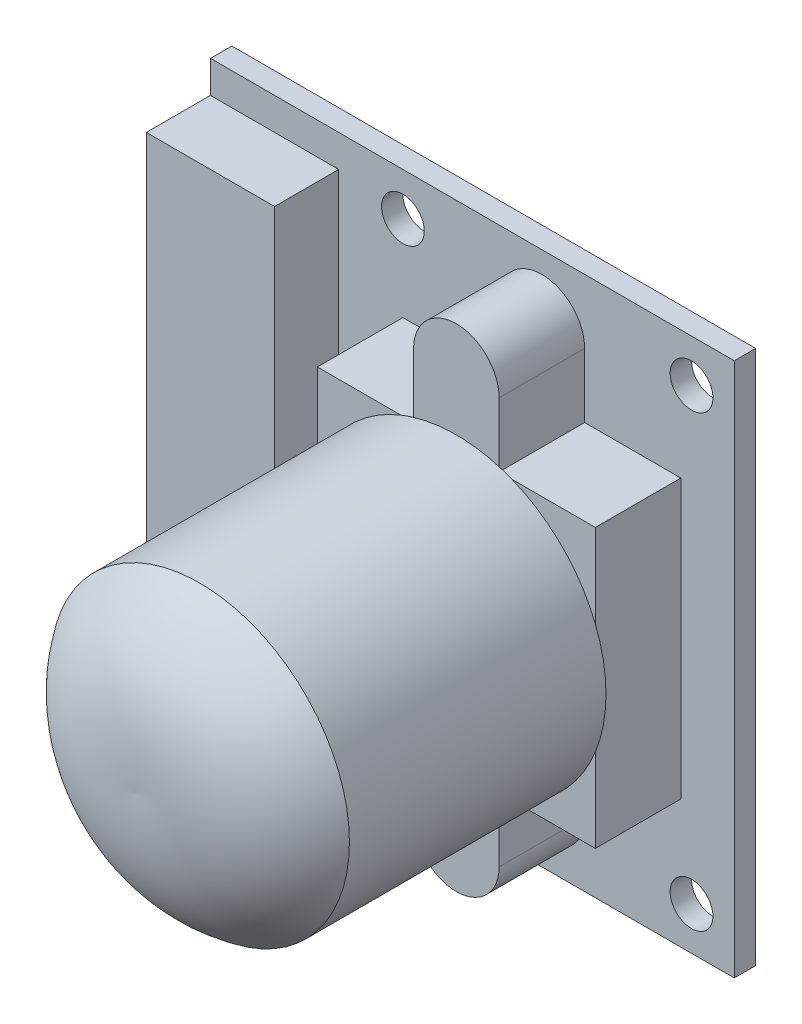
SolidWorks part; units mm, degrees
ref_plane "Front Plane" through (0, 0, 0) normal (0, 0, 1) x (1, 0, 0)
ref_plane "Top Plane" through (0, 0, 0) normal (0, 1, 0) x (1, 0, 0)
ref_plane "Right Plane" through (0, 0, 0) normal (1, 0, 0) x (0, 0, -1)
sketch "Sketch1" plane through (0, 0, 0) normal (0, 0, 1) x (1, 0, 0)
  line L1 (-12.25, -12.5) -> (12.25, -12.5)
  line L2 (-12.25, -12.5) -> (-12.25, 12.5)
  line L3 (-12.25, 12.5) -> (12.25, 12.5)
  line L4 (12.25, -12.5) -> (12.25, 12.5)
  line L5 (-12.25, -12.5) -> (12.25, 12.5) construction
  line L6 (-12.25, 12.5) -> (12.25, -12.5) construction
  point P0 (0, 0)
  dimension "D1" = 24.5
  dimension "D2" = 25
extrude "Boss-Extrude1" add sketch "Sketch1" along normal blind 1
sketch "Sketch2" plane through (0, 0, 1) normal (0, 0, 1) x (1, 0, 0)
  line L0 (-12.25, 12.5) -> (-12.25, -12.5) construction
  line L1 (-18.25, -11) -> (-6.25, -11)
  line L2 (-18.25, -11) -> (-18.25, 11)
  line L3 (-18.25, 11) -> (-6.25, 11)
  line L4 (-6.25, -11) -> (-6.25, 11)
  line L5 (-18.25, -11) -> (-6.25, 11) construction
  line L6 (-18.25, 11) -> (-6.25, -11) construction
  line L7 (-12.25, 11) -> (-12.25, -11)
  point P0 (-12.25, 0)
  line M5 (-12.25, 12.5) -> (-12.25, -12.5)
  dimension "D1" = 12
  dimension "D2" = 22
extrude "Boss-Extrude2" add sketch "Sketch2" along normal blind 3 contours L1 L4 L3 M5
sketch "Sketch3" plane through (0, 0, 1) normal (0, 0, 1) x (1, 0, 0)
  line L0 (12.25, 12.5) -> (-12.25, 12.5) construction
  line L2 (12.25, -12.5) -> (12.25, 12.5) construction
  circle A0 centre (10.25, 10.5) radius 1
  circle A1 centre (10.25, -10.5) radius 1
  circle A2 centre (-3.25, 10.5) radius 1
  circle A3 centre (-3.25, -10.5) radius 1
  dimension "D3" = 2
  dimension "D4" = 2
  dimension "D7" = 2
  dimension "D8" = 2
  dimension "D1" = 21
  dimension "D2" = 2
  dimension "D5" = 13.5
  dimension "D6" = 13.5
  dimension "D9" = 2
extrude "Cut-Extrude1" cut sketch "Sketch3" against normal through all
sketch "Sketch4" plane through (0, 0, 1) normal (0, 0, 1) x (1, 0, 0)
  line L0 (5.25, 9.5) -> (5.25, 6.5)
  line L1 (-3.25, 6.5) -> (9.75, 6.5)
  line L2 (-3.25, 6.5) -> (-3.25, -6.5)
  line L3 (-3.25, -6.5) -> (9.75, -6.5)
  line L4 (9.75, 6.5) -> (9.75, -6.5)
  line L5 (-3.25, 6.5) -> (9.75, -6.5) construction
  line L6 (-3.25, -6.5) -> (9.75, 6.5) construction
  line L7 (1.25, 9.5) -> (1.25, 6.5)
  line L8 (-3.25, 0) -> (-7.8918, 0)
  line L9 (1.25, -9.5) -> (1.25, -6.5)
  line L10 (5.25, -9.5) -> (5.25, -6.5)
  circle A0 centre (10.25, 10.5) radius 1 construction
  circle A1 centre (3.25, 9.5) radius 2
  circle A2 centre (3.25, -9.5) radius 2
  point P0 (3.25, 0)
  dimension "D3" = 7
  dimension "D4" = 4
  dimension "D2" = 13
  dimension "D5" = 3
  dimension "D6" = 13
extrude "Boss-Extrude3" add sketch "Sketch4" along normal blind 4 contours A1 | A1 L7 L1 L0 | L4 L1 L2 L3 | A2 | L9 A2 L10 L3
sketch "Sketch5" plane through (0, 0, 5) normal (0, 0, 1) x (1, 0, 0)
  circle A0 centre (3.25, 0) radius 7
  dimension "D1" = 14
extrude "Boss-Extrude4" add sketch "Sketch5" along normal blind 12
sketch "Sketch7" plane through (0, 0, 0) normal (0, 1, 0) x (1, 0, 0)
  line L0 (3.25, -17) -> (3.25, -20)
  line L1 (-3.75, -17) -> (10.25, -17) construction
  line L2 (3.25, -17) -> (-3.75, -17)
  spline S0 degree 2 poles (-3.75, -17) (-1.5211, -20.2649) (3.25, -20) knots 0 0 0 1 1 1
  dimension "D1" = 3
  dimension "D2" = 7
revolve "Revolve1" add sketch "Sketch7" angle 360 about L0
sketch "Sketch8" plane through (0, 0, 1) normal (0, 0, 1) x (1, 0, 0)
  circle A0 centre (3.25, 0) radius 7 construction
  circle A1 centre (3.25, 0) radius 7
  point P4 (3.25, 0)
  point P5 (3.25, 0)
